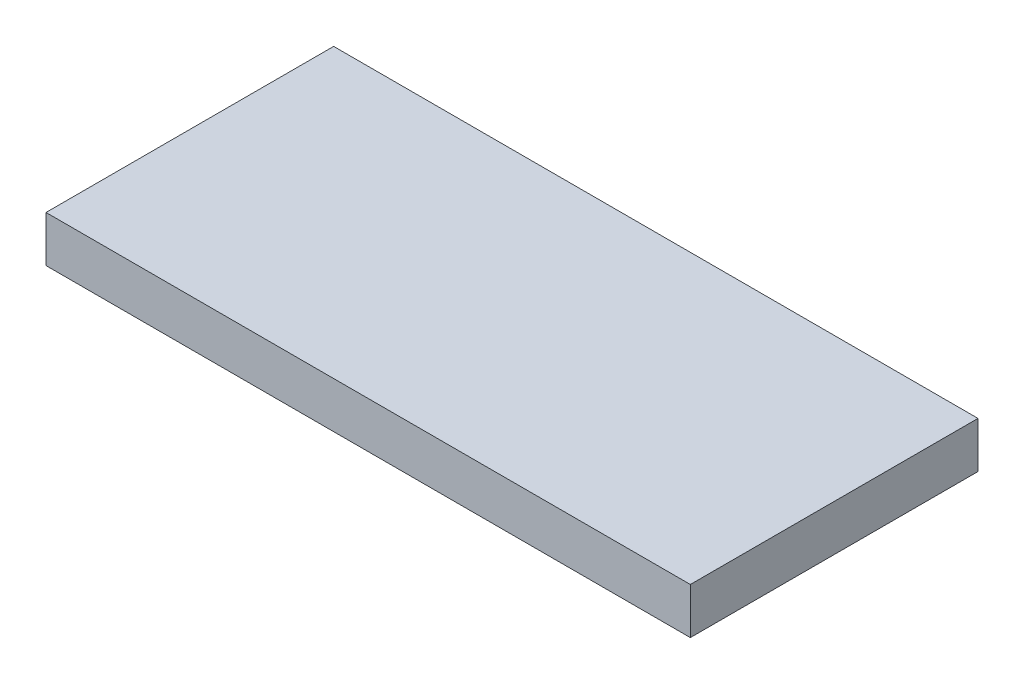
SolidWorks part; units mm, degrees
ref_plane "前视基准面" through (0, 0, 0) normal (0, 0, 1) x (1, 0, 0)
ref_plane "上视基准面" through (0, 0, 0) normal (0, 1, 0) x (1, 0, 0)
ref_plane "右视基准面" through (0, 0, 0) normal (1, 0, 0) x (0, 0, -1)
other "Configuration Table"
sketch "草图1" plane through (0, 0, 0) normal (0, 0, 1) x (1, 0, 0)
  line L0 (0, 0) -> (56, 0)
  line L1 (56, 0) -> (56, 4)
  line L2 (56, 4) -> (0, 4)
  line L3 (0, 4) -> (0, 0)
  dimension "width" = 56
  dimension "height" = 4
extrude "Top_mount_bridge" add sketch "草图1" along normal blind 25
